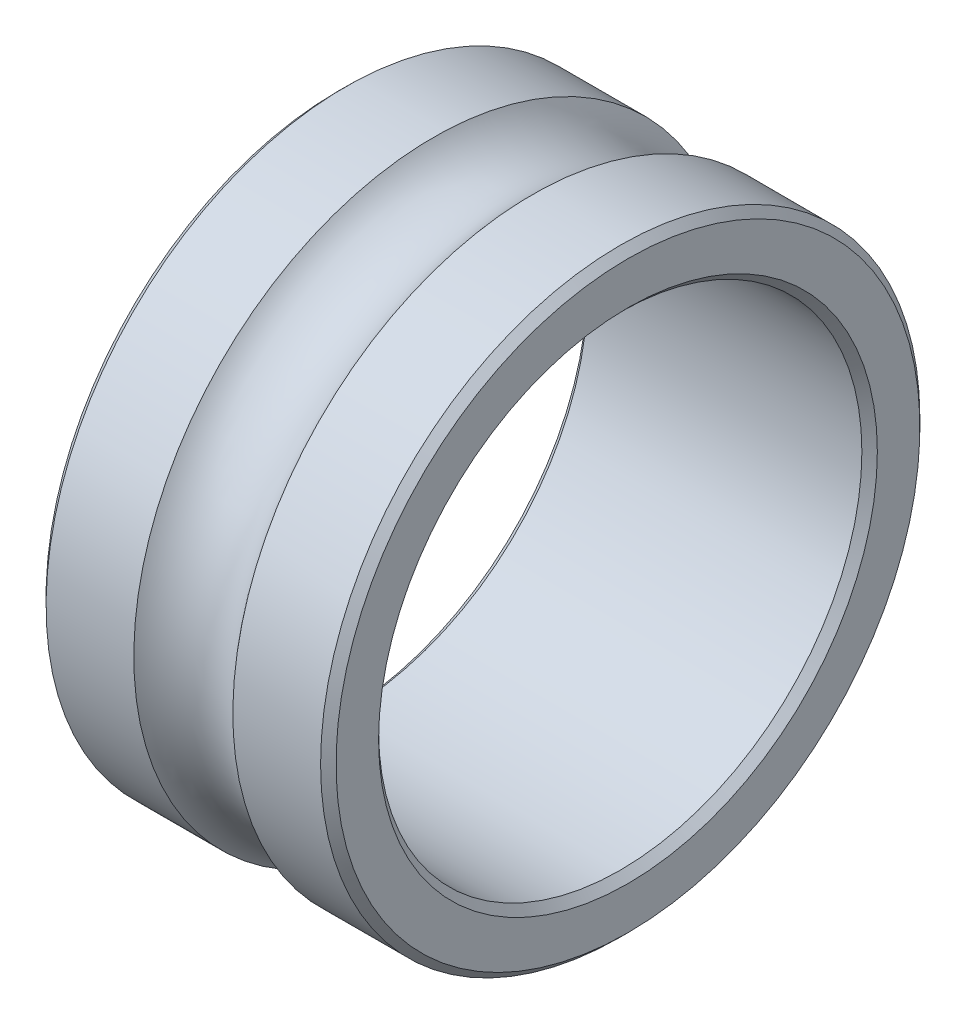
SolidWorks part; units mm, degrees
ref_plane "Front" through (0, 0, 0) normal (0, 0, 1) x (1, 0, 0)
ref_plane "Top" through (0, 0, 0) normal (0, 1, 0) x (1, 0, 0)
ref_plane "Right" through (0, 0, 0) normal (1, 0, 0) x (0, 0, -1)
sketch "Sketch1" plane through (0, 0, 0) normal (0, 0, 1) x (1, 0, 0)
  line L0 (-6.429, 0) -> (6.429, 0) construction
  line L3 (0.5123, -3.1) -> (1.5, -3.1)
  line L6 (0, -2.5) -> (0, -4.5) construction
  line L17 (-1.5, -3.9) -> (1.5, -3.9) construction
  line L18 (-1.5, -2.5) -> (1.5, -2.5)
  line L19 (-1.5, -2.5) -> (-1.5, -3.1)
  line L20 (-1.5, -3.1) -> (-0.5123, -3.1)
  line L21 (1.5, -2.5) -> (1.5, -3.1)
  line L22 (-1.5, -4.5) -> (1.5, -4.5) construction
  circle A0 centre (0, -3.5) radius 0.65 construction
  arc A1 (-0.5123, -3.1) -> (0.5123, -3.1) centre (0, -3.5) cw
  point P13 (0, -3.5)
  point P26 (0, 0)
  dimension "D3" = 1.3
  dimension "D6" = 4.5
  dimension "D1" = 0.6
  dimension "D2" = 2.5
  dimension "D4" = 3
  dimension "D5" = 0.6
revolve "Revolve1" add sketch "Sketch1" angle 360 about L0
chamfer "Chamfer2" distance 0.08 angle 45 4 edges at (1.5, -3.1, 0) (1.5, -2.5, 0) (-1.5, -2.5, 0) (-1.5, -3.1, 0)
